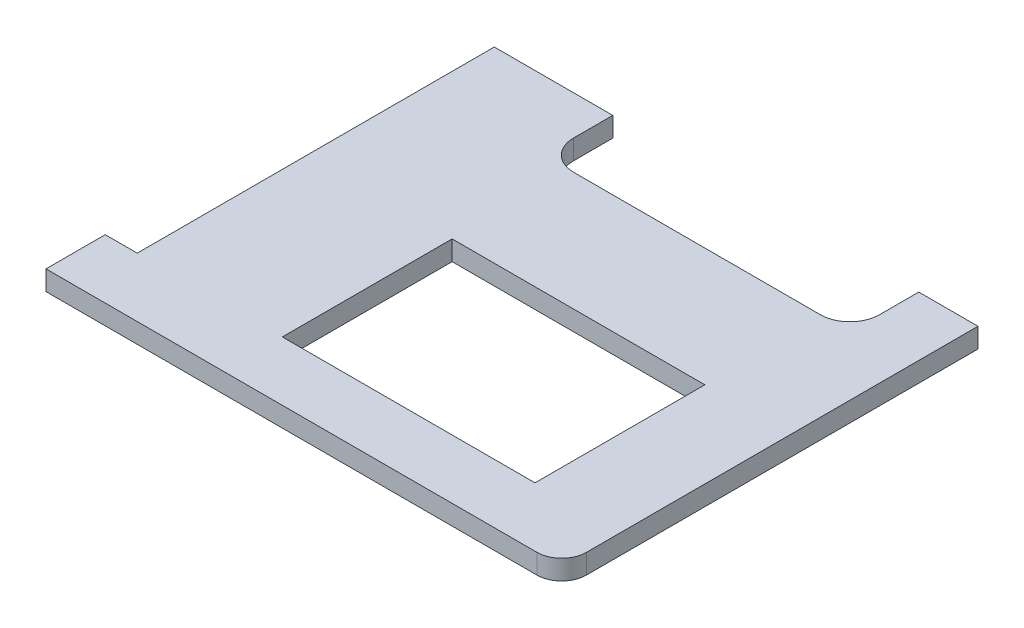
SolidWorks part; units mm, degrees
ref_plane "Front Plane" through (0, 0, 0) normal (0, 0, 1) x (1, 0, 0)
ref_plane "Top Plane" through (0, 0, 0) normal (0, 1, 0) x (1, 0, 0)
ref_plane "Right Plane" through (0, 0, 0) normal (1, 0, 0) x (0, 0, -1)
sketch "Sketch1" plane through (0, 0, 0) normal (0, 1, 0) x (1, 0, 0)
  line L0 (-62.5, -77.5) -> (62.5, -77.5) construction
  line L1 (-62.5, -77.5) -> (62.5, -77.5)
  line L2 (-77.5, -62.5) -> (-77.5, 62.5)
  line L3 (-62.5, 77.5) -> (62.5, 77.5)
  line L4 (77.5, -62.5) -> (77.5, 62.5)
  line L5 (-77.5, -77.5) -> (77.5, 77.5) construction
  line L6 (-77.5, 77.5) -> (77.5, -77.5) construction
  arc A0 (-62.5, -77.5) -> (-77.5, -62.5) centre (-62.5, -62.5) cw
  arc A1 (62.5, -77.5) -> (77.5, -62.5) centre (62.5, -62.5) ccw
  arc A2 (-77.5, 62.5) -> (-62.5, 77.5) centre (-62.5, 62.5) cw
  arc A3 (62.5, 77.5) -> (77.5, 62.5) centre (62.5, 62.5) cw
  point P0 (0, 0)
  dimension "D2" = 15
  dimension "D1" = 155
sketch "Sketch3" plane through (0, 0, 0) normal (0, 1, 0) x (1, 0, 0)
  line L0 (-64, -223.5) -> (64, -223.5)
  line L1 (-64, -223.5) -> (-64, -137.5)
  line L2 (-64, -137.5) -> (64, -137.5)
  line L3 (64, -223.5) -> (64, -137.5)
  line L4 (-64, -137.5) -> (64, -223.5) construction
  line L5 (64, -137.5) -> (-64, -223.5) construction
  line L6 (0, 0) -> (0, -262.1998) construction
  line L7 (-77.5, 77.5) -> (77.5, -77.5) construction
  line L8 (-62.5, -77.5) -> (62.5, -77.5) construction
  line L9 (-77.5, -62.5) -> (-77.5, 62.5) construction
  line L10 (-203.5, -223.5) -> (-137.5, -223.5)
  line L11 (-203.5, -223.5) -> (-203.5, -11.5)
  line L12 (-203.5, -11.5) -> (-137.5, -11.5)
  line L13 (-137.5, -223.5) -> (-137.5, -11.5)
  line L14 (-203.5, -223.5) -> (-137.5, -11.5) construction
  line L15 (-203.5, -11.5) -> (-137.5, -223.5) construction
  point P8 (0, -180.5)
  point P11 (-170.5, -117.5)
  dimension "D1" = 60
  dimension "D2" = 86
  dimension "D3" = 128
  dimension "D4" = 0
  dimension "D5" = 60
  dimension "D6" = 66
  dimension "D7" = 212
sketch "Sketch4" plane through (0, 0, 0) normal (0, 1, 0) x (1, 0, 0)
  line L0 (-221, 107.5) -> (95, 107.5)
  line L1 (-233.5, 95) -> (-233.5, -241)
  line L2 (-221, -253.5) -> (95, -253.5)
  line L3 (107.5, 95) -> (107.5, -241)
  line L4 (-203.5, -223.5) -> (-203.5, -11.5) construction
  line L5 (-203.5, -223.5) -> (-137.5, -223.5) construction
  line L6 (-62.5, 77.5) -> (62.5, 77.5) construction
  line L7 (77.5, -62.5) -> (77.5, 62.5) construction
  arc A0 (95, 107.5) -> (107.5, 95) centre (95, 95) cw
  arc A1 (95, -253.5) -> (107.5, -241) centre (95, -241) ccw
  arc A2 (-233.5, -241) -> (-221, -253.5) centre (-221, -241) ccw
  arc A3 (-221, 107.5) -> (-233.5, 95) centre (-221, 95) ccw
  dimension "D1" = 30
  dimension "D2" = 30
  dimension "D3" = 30
  dimension "D4" = 30
extrude "Boss-Extrude1" add sketch "Sketch4" along normal blind 10
extrude "Cut-Extrude1" cut sketch "Sketch3" along normal through all
extrude "Cut-Extrude2" cut sketch "Sketch1" along normal through all
sketch "Sketch6" plane through (0, 0, 0) normal (0, 1, 0) x (1, 0, 0)
  line L0 (-233.5, 95) -> (-233.5, -241) construction
  line L1 (-233.5, -42.6356) -> (110, -42.6356)
  line L2 (-233.5, -42.6356) -> (-233.5, 116.3862)
  line L3 (-233.5, 116.3862) -> (110, 116.3862)
  line L4 (110, -42.6356) -> (110, 116.3862)
extrude "Cut-Extrude3" cut sketch "Sketch6" along normal through all
sketch "Sketch7" plane through (0, 0, 0) normal (0, 1, 0) x (1, 0, 0)
  line L0 (-221, -253.5) -> (95, -253.5) construction
  line L2 (-153.7068, -253.5) -> (-240.6024, -253.5)
  line L3 (-153.7068, -253.5) -> (-153.7068, -29.0741)
  line L4 (-153.7068, -29.0741) -> (-240.6024, -29.0741)
  line L5 (-240.6024, -253.5) -> (-240.6024, -29.0741)
extrude "Cut-Extrude4" cut sketch "Sketch7" along normal through all
